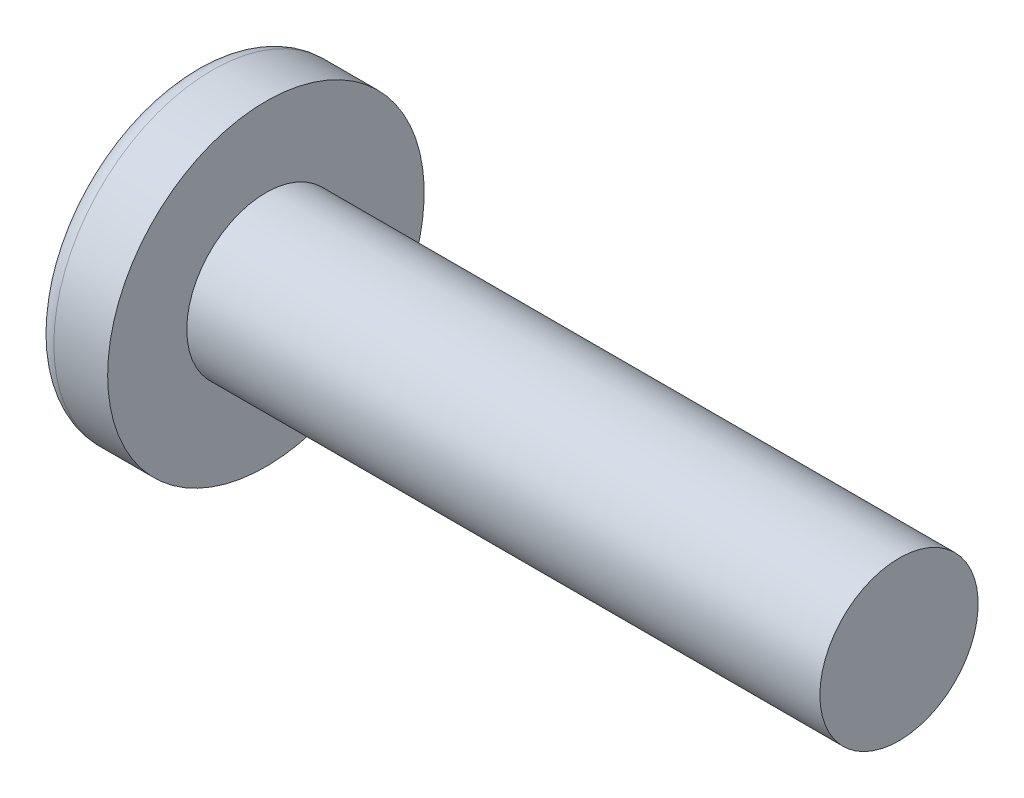
SolidWorks part; units mm, degrees
ref_plane "Plane1" through (0, 0, 0) normal (0, 0, 1) x (1, 0, 0)
ref_plane "Plane2" through (0, 0, 0) normal (0, 1, 0) x (1, 0, 0)
ref_plane "Plane3" through (0, 0, 0) normal (1, 0, 0) x (0, 0, -1)
sketch "BodySke" plane through (0, 0, 0) normal (0, 0, 1) x (1, 0, 0)
  line L0 (7.5, 5) -> (7.5, 10)
  line L1 (9, 6.35) -> (9, -3.175) construction
  line L2 (-25.4, 0) -> (127, 0) construction
  line L3 (47.5, 0) -> (0, 0)
  line L4 (7.5, 5) -> (47.5, 5)
  line L5 (47.5, 5) -> (47.5, 0)
  line L6 (4.1004, 10) -> (7.5, 10)
  line L7 (7.5, -5) -> (47.5, -5) construction
  line L8 (7.5, 6.35) -> (7.5, -3.175) construction
  arc A0 (3.1356, 9.5135) -> (0, 0) centre (16, 0) ccw
  arc A2 (3.1356, 9.5135) -> (4.1004, 10) centre (4.1004, 8.8) cw
  dimension "Head_fillet_rad" = 1.2
  dimension "Head_crown_rad" = 16
  dimension "Head_ht" = 7.5
  dimension "Diameter" = 10
  dimension "Length" = 40
  dimension "Head_dia" = 20
  dimension "Advance" = 1.5
  dimension "Thread_nom" = 40
revolve "Base-Revolve" add sketch "BodySke" angle 360 about L2
cosmetic thread "ThreadCosmetic" [suppressed] parameters "Thread_length"=38.5, "Thread_minor"=8.344
sketch "Sketch3" plane through (0, 0, 0) normal (1, 0, 0) x (0, 0, -1)
  line L0 (0.92, -5.09) -> (-0.92, -5.09)
  line L1 (0.92, -5.09) -> (0.92, 5.09)
  line L2 (-0.92, 5.09) -> (0.92, 5.09)
  line L3 (-0.92, 5.09) -> (-0.92, -5.09)
  dimension "D1" = 5.09
  dimension "Cross_dia" = 10.18
  dimension "D2" = 0.92
  dimension "Cross_width" = 1.84
ref_plane "Plane4" through (6.09, 0, 0) normal (1, 0, 0) x (0, 0, -1)
sketch "Sketch4" plane through (6.09, 0, 0) normal (1, 0, 0) x (0, 0, -1)
  line L0 (0.46, -0.46) -> (-0.46, -0.46)
  line L1 (0.46, -0.46) -> (0.46, 0.46)
  line L2 (-0.46, 0.46) -> (0.46, 0.46)
  line L3 (-0.46, 0.46) -> (-0.46, -0.46)
  dimension "D1" = 0.92
  dimension "D2" = 0.92
  dimension "D3" = 0.46
  dimension "D4" = 0.46
loft "Cut-Loft1" cut profiles "Sketch3", "Sketch4"
pattern_circular "CirPattern1" count 2 every 90 about axis through (0, 0, 0) along (1, 0, 0) of "Cut-Loft1"
sketch "ThdSchSke" plane through (0, 0, 0) normal (0, 0, 1) x (1, 0, 0)
  line L0 (9, -4.172) -> (8.4202, -5)
  line L1 (9, -4.172) -> (9.5798, -5)
  line L2 (9.5798, -5) -> (9.5798, -6.25)
  line L3 (-3.175, 0) -> (5.1513, 0) construction
  line L5 (9.5798, -6.25) -> (8.4202, -6.25)
  line L6 (8.4202, -6.25) -> (8.4202, -5)
  dimension "Thread_minor" = 8.344
  dimension "Diameter" = 10
  dimension "Start" = 9
  dimension "SideAngle" = 55
  dimension "VeeAngle" = 70
  dimension "Overcut" = 12.5
revolve "ThreadSchematic" [suppressed] cut sketch "ThdSchSke" angle 360 about L3
pattern_linear "ThdSchPat" [suppressed]
equation "\"D1@Sketch3\" = \"Cross_dia@Sketch3\" / 2"
equation "\"D2@Sketch3\" = \"Cross_width@Sketch3\" / 2"
equation "\"D1@Sketch4\" = \"Cross_width@Sketch3\" *.5"
equation "\"D2@Sketch4\" = \"D1@Sketch4\""
equation "\"D3@Sketch4\" = \"D1@Sketch4\" / 2"
equation "\"D4@Sketch4\" = \"D2@Sketch4\" / 2"
equation "\"Thread_length@ThreadCosmetic\" = ((sgn( (\"Length@BodySke\" - \"Advance@BodySke\" ) - \"Thread_nom@BodySke\" )-1)*( (\"Length@BodySke\" - \"Advance@BodySke\" ) - \"Thread_nom@BodySke\" ))/-2+ \"Thread_nom@BodySke\""
equation "\"Thread_minor@ThdSchSke\" = \"Thread_minor@ThreadCosmetic\""
equation "\"Diameter@ThdSchSke\" = \"Diameter@BodySke\""
equation "\"Overcut@ThdSchSke\" = \"Diameter@BodySke\" * 1.25"
equation "\"Start@ThdSchSke\" = \"Head_ht@BodySke\" + \"Length@BodySke\" - \"Thread_length@ThreadCosmetic\"  '---Non-countersunk---"
equation "\"Num_threads@ThdSchPat\" = int( \"Thread_length@ThreadCosmetic\" / \"Advance@BodySke\" + 0.999 )  + 1"
equation "\"Advance@ThdSchPat\" = \"Thread_length@ThreadCosmetic\" /  (\"Num_threads@ThdSchPat\" - 1) 'relax it"
